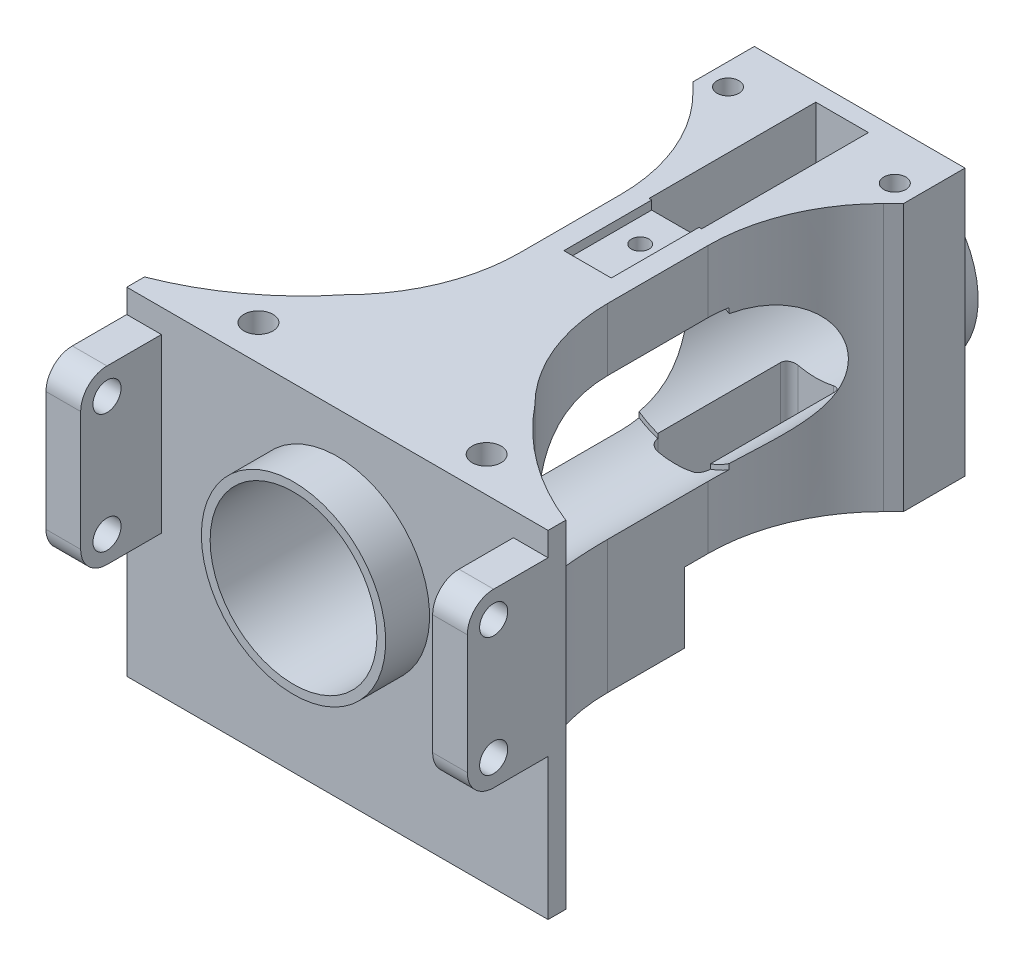
SolidWorks part; units mm, degrees
material "6061 合金"
ref_plane "前视基准面" through (0, 0, 0) normal (0, 0, 1) x (1, 0, 0)
ref_plane "上视基准面" through (0, 0, 0) normal (0, 1, 0) x (1, 0, 0)
ref_plane "右视基准面" through (0, 0, 0) normal (1, 0, 0) x (0, 0, -1)
sketch "草图1" plane through (0, 0, 0) normal (0, 0, 1) x (1, 0, 0)
  line L1 (-24, -15.2) -> (24, -15.2)
  line L2 (-24, -15.2) -> (-24, 15.2)
  line L3 (-24, 15.2) -> (24, 15.2)
  line L4 (24, -15.2) -> (24, 15.2)
  line L5 (-24, -15.2) -> (24, 15.2) construction
  line L6 (-24, 15.2) -> (24, -15.2) construction
  circle A0 centre (0, 0) radius 9
  point P0 (0, 0)
  dimension "D3" = 18
  dimension "D1" = 48
  dimension "D2" = 30.4
extrude "凸台-拉伸1" add sketch "草图1" along normal blind 65
sketch "草图2" plane through (0, 0, 65) normal (0, 0, 1) x (1, 0, 0)
  circle A0 centre (0, 0) radius 9.5
  dimension "D1" = 19
extrude "切除-拉伸1" cut sketch "草图2" against normal offset from surface (49 mm away) 16 up to face at (0, 0, 0)
sketch "草图4" plane through (0, 15.2, 0) normal (0, 1, 0) x (1, 0, 0)
  line L0 (-24, 9) -> (-10.8579, -4.1421)
  line L1 (-24, -65) -> (-24, 0) construction
  line L2 (-5, -18.2843) -> (-5, -29.7157)
  line L3 (-10.8579, -43.8579) -> (-24, -57) construction
  line L4 (-24, -57) -> (-24, 9) construction
  line L5 (0, 0) -> (0, -65) construction
  line L6 (24, -65) -> (-24, -65) construction
  line L7 (-24, -65) -> (-24, -62) construction
  line L8 (-24, -62) -> (-21, -62) construction
  line L9 (24, 0) -> (-24, 0) construction
  line L10 (10.8579, -43.8579) -> (24, -57) construction
  line L11 (5, -18.2843) -> (5, -29.7157)
  line L12 (24, 9) -> (10.8579, -4.1421)
  line L13 (24, -57) -> (24, 9) construction
  line L14 (35.5, -24) -> (-35.5, -24) construction
  line L15 (9.5, -2.5) -> (-9.5, -2.5) construction
  line L16 (24, -53.4842) -> (24, 9)
  line L17 (-24, -53.4842) -> (-24, 9)
  arc A2 (5, -18.2843) -> (10.8579, -4.1421) centre (25, -18.2843) cw
  arc A3 (10.8579, -43.8579) -> (5, -29.7157) centre (25, -29.7157) cw
  arc A4 (-5, -29.7157) -> (-10.8579, -43.8579) centre (-25, -29.7157) cw
  arc A5 (-10.8579, -4.1421) -> (-5, -18.2843) centre (-25, -18.2843) cw
  circle A6 centre (-35.5, -24) radius 30 construction
  circle A7 centre (35.5, -24) radius 30 construction
  circle A8 centre (9.5, -2.5) radius 1.2 construction
  circle A9 centre (-9.5, -2.5) radius 1.2 construction
  arc A10 (-10.8579, -43.8579) -> (-24, -53.4842) centre (-35.5, -24) cw
  arc A11 (10.8579, -43.8579) -> (24, -53.4842) centre (35.5, -24) ccw
  point P12 (-5, -24)
  point P26 (5, -10)
  point P29 (5, -38)
  point P32 (-5, -38)
  point P35 (-5, -10)
  point P36 (0, -24)
  point P41 (0, -2.5)
  dimension "D3" = 24
  dimension "D7" = 20
  dimension "D4" = 60
  dimension "D11" = 2.4
  dimension "D1" = 3
  dimension "D2" = 3
  dimension "D5" = 10
  dimension "D6" = 10
  dimension "D8" = 71
  dimension "D9" = 2.5
  dimension "D10" = 19
  dimension "D12" = 135
extrude "切除-拉伸3" cut sketch "草图4" against normal through all
sketch "草图6" plane through (0, 15.2, 0) normal (0, 1, 0) x (1, 0, 0)
  line L0 (0, 0) -> (0, -1) construction
  line L1 (-2, -1) -> (2, -1)
  line L2 (-3, -2) -> (-3, -16)
  line L3 (-2, -17) -> (2, -17)
  line L4 (3, -2) -> (3, -16)
  line L8 (-5, -18.2843) -> (5, -18.2843) construction
  arc A0 (-3, -16) -> (-2, -17) centre (-2, -16) ccw
  arc A1 (2, -17) -> (3, -16) centre (2, -16) ccw
  arc A2 (2, -1) -> (3, -2) centre (2, -2) cw
  arc A3 (-2, -1) -> (-3, -2) centre (-2, -2) ccw
  point P9 (-3, -17)
  point P14 (3, -1)
  point P17 (-3, -1)
  dimension "D4" = 1
  dimension "D1" = 1
  dimension "D2" = 16
  dimension "D3" = 6
extrude "切除-拉伸5" cut sketch "草图6" along normal through all from surface at -30.4 starting at face at (0, -15.2, 30.7635)
sketch "草图12" plane through (0, -15.2, 0) normal (0, -1, 0) x (1, 0, 0)
  line L0 (-5, 18.2843) -> (5, 18.2843)
  line L12 (-15, 0) -> (15, 0)
  line L14 (15, 0) -> (10.8579, 4.1421)
  line L15 (5, 18.2843) -> (5, 29.7157)
  line L17 (24, 53.4842) -> (24, 65)
  line L18 (24, 65) -> (-24, 65)
  line L19 (-24, 65) -> (-24, 53.4842)
  line L21 (-5, 29.7157) -> (-5, 18.2843)
  line L22 (-10.8579, 4.1421) -> (-15, 0)
  line L24 (-15, 0) -> (15, 0) construction
  line L26 (15, 0) -> (10.8579, 4.1421) construction
  line L27 (5, 18.2843) -> (5, 29.7157)
  line L29 (24, 53.4842) -> (24, 65)
  line L30 (24, 65) -> (-24, 65)
  line L31 (-24, 65) -> (-24, 53.4842)
  line L33 (-5, 29.7157) -> (-5, 18.2843)
  line L34 (-10.8579, 4.1421) -> (-15, 0) construction
  arc A4 (5, 18.2843) -> (10.8579, 4.1421) centre (25, 18.2843) ccw
  arc A5 (10.8579, 43.8579) -> (5, 29.7157) centre (25, 29.7157) ccw
  arc A6 (-5, 29.7157) -> (-10.8579, 43.8579) centre (-25, 29.7157) ccw
  arc A7 (-10.8579, 4.1421) -> (-5, 18.2843) centre (-25, 18.2843) ccw
  arc A8 (5, 18.2843) -> (10.8579, 4.1421) centre (25, 18.2843) ccw construction
  arc A9 (10.8579, 43.8579) -> (5, 29.7157) centre (25, 29.7157) ccw
  arc A10 (-5, 29.7157) -> (-10.8579, 43.8579) centre (-25, 29.7157) ccw
  arc A11 (-10.8579, 4.1421) -> (-5, 18.2843) centre (-25, 18.2843) ccw construction
  arc A14 (24, 53.4842) -> (10.8579, 43.8579) centre (35.5, 24) ccw
  arc A15 (24, 53.4842) -> (10.8579, 43.8579) centre (35.5, 24) ccw
  arc A16 (-10.8579, 43.8579) -> (-24, 53.4842) centre (-35.5, 24) ccw
  arc A17 (-10.8579, 43.8579) -> (-24, 53.4842) centre (-35.5, 24) ccw
  dimension "D1" = 0
extrude "凸台-拉伸4" add sketch "草图12" along normal blind 8
sketch "草图11" plane through (0, 15.2, 0) normal (0, 1, 0) x (1, 0, 0)
  line L0 (13, -51.5) -> (-13, -51.5) construction
  line L1 (0, -51.5) -> (0, 0) construction
  circle A0 centre (13, -51.5) radius 1.65
  circle A1 centre (-13, -51.5) radius 1.65
  dimension "D3" = 3.3
  dimension "D1" = 51.5
  dimension "D2" = 26
extrude "切除-拉伸9" cut sketch "草图11" against normal through all
cosmetic thread "装饰螺纹线5" parameters "D2"=4
cosmetic thread "装饰螺纹线6" parameters "D2"=4
cosmetic thread "装饰螺纹线7" parameters "D2"=4
cosmetic thread "装饰螺纹线8" parameters "D2"=4
sketch "草图14" plane through (0, -23.2, 0) normal (0, -1, 0) x (1, 0, 0)
  line L0 (-5, 24) -> (5, 24) construction
  line L1 (-5, 29.7157) -> (-5, 18.2843) construction
  line L2 (5, 18.2843) -> (5, 29.7157) construction
  circle A0 centre (0, 24) radius 1.65
  dimension "D1" = 3.3
extrude "切除-拉伸10" cut sketch "草图14" against normal blind 11
cosmetic thread "装饰螺纹线9" parameters "D2"=4
sketch "草图15" plane through (0, 15.2, 0) normal (0, 1, 0) x (1, 0, 0)
  line L0 (24, -65) -> (-24, -65) construction
  line L1 (20.05, -65) -> (-20.05, -65)
  line L2 (20.05, -65) -> (20.05, -55.5)
  line L3 (20.05, -55.5) -> (-20.05, -55.5)
  line L4 (-20.05, -65) -> (-20.05, -55.5)
  line L5 (0, 0) -> (0, -55.5) construction
  circle A0 centre (-13, -51.5) radius 1.65 construction
  dimension "D1" = 40.1
  dimension "D2" = 4
extrude "切除-拉伸11" cut sketch "草图15" against normal through all
sketch "草图17" plane through (24, 0, 0) normal (1, 0, 0) x (0, 0, -1)
  line L0 (-53.4842, -23.2) -> (-65, -23.2) construction
  line L1 (-65, 15.2) -> (-53.4842, 15.2) construction
  line L2 (-61.7, 9.5) -> (-61.7, -4.1) construction
  line L3 (-61.7, 2.7) -> (-55.5, 2.7) construction
  line L4 (-55.5, -23.2) -> (-55.5, -7.1)
  line L5 (-55.5, -7.1) -> (-61.7, -7.1)
  line L6 (-64.7, -4.1) -> (-64.7, 9.5)
  line L9 (-64.7, 15.2) -> (-93.9, 15.2)
  line L10 (-93.9, 15.2) -> (-93.9, -23.2)
  line L11 (-93.9, -23.2) -> (-55.5, -23.2)
  line L12 (-55.5, -23.2) -> (-55.5, 15.2) construction
  line L13 (-61.7, 12.5) -> (-55.5, 12.5)
  line L14 (-55.5, 12.5) -> (-55.5, 15.2)
  line L15 (-55.5, 15.2) -> (-64.7, 15.2)
  circle A0 centre (-61.7, 9.5) radius 1.6
  circle A1 centre (-61.7, -4.1) radius 1.6
  arc A3 (-61.7, -7.1) -> (-64.7, -4.1) centre (-61.7, -4.1) cw
  arc A4 (-61.7, 12.5) -> (-64.7, 9.5) centre (-61.7, 9.5) ccw
  dimension "D3" = 3.2
  dimension "D4" = 3
  dimension "D1" = 13.6
  dimension "D2" = 6.2
  dimension "D6" = 12.5
extrude "切除-拉伸13" cut sketch "草图17" against normal through all
sketch "草图19" plane through (0, -15.2, 0) normal (0, -1, 0) x (1, 0, 0)
  line L0 (-10.8579, 4.1421) -> (-15, 0) construction
  line L1 (-15, 0) -> (-12, 0)
  line L2 (-15, 0) -> (-15, 3)
  line L3 (-15, 3) -> (-12, 3)
  line L4 (-12, 0) -> (-12, 3)
  line L5 (15, 0) -> (10.8579, 4.1421) construction
  line L6 (15, 0) -> (12, 0)
  line L7 (15, 0) -> (15, 3)
  line L8 (15, 3) -> (12, 3)
  line L9 (12, 0) -> (12, 3)
  dimension "D1" = 3
extrude "切除-拉伸14" cut sketch "草图19" against normal through all
sketch "草图21" plane through (0, 0, 18.2843) normal (0, 0, -1) x (-1, 0, 0)
  line L1 (5, -23.2) -> (-5, -23.2)
  line L2 (5, -23.2) -> (5, -15.2)
  line L3 (5, -15.2) -> (-5, -15.2)
  line L4 (-5, -23.2) -> (-5, -15.2)
  line L5 (0, -15.2) -> (0, -23.2) construction
  line L6 (5, -19.2) -> (-5, -19.2) construction
  point P164 (0, -19.2)
extrude "切除-拉伸16" cut sketch "草图21" against normal blind 2.7
sketch "草图24" plane through (0, -15.2, 0) normal (0, -1, 0) x (1, 0, 0)
  line L0 (-12, 1.5) -> (12, 1.5) construction
  line L1 (-12, 0) -> (-12, 3) construction
  line L2 (12, 3) -> (12, 0) construction
  line L3 (-12, 0) -> (12, 0) construction
  circle A0 centre (-9.5, 1.5) radius 1.25
  circle A1 centre (9.5, 1.5) radius 1.25
  dimension "D2" = 2.5
  dimension "D3" = 2.5
  dimension "D4" = 2.5
  dimension "D1" = 1.5
extrude "切除-拉伸17" cut sketch "草图24" against normal through all
cosmetic thread "装饰螺纹线10" parameters "D2"=3
cosmetic thread "装饰螺纹线11" parameters "D2"=3
sketch "草图25" plane through (0, 0, 55.5) normal (0, 0, 1) x (1, 0, 0)
  circle A0 centre (0, 0) radius 9.5 construction
  circle A1 centre (0, 0) radius 9.5
  circle A2 centre (0, 0) radius 10.5
  dimension "D1" = 21
extrude "凸台-拉伸6" add sketch "草图25" along normal blind 86.25
sketch "草图27" plane through (-24, 0, 0) normal (-1, 0, 0) x (0, 0, 1)
  line L0 (141.75, -10.5) -> (141.75, 10.5) construction
  line L1 (141.75, 0) -> (0, 0) construction
  circle A0 centre (129.75, 0) radius 4
  circle A1 centre (78.75, 0) radius 4
  dimension "D1" = 8
  dimension "D2" = 12
  dimension "D3" = 63
extrude "切除-拉伸18" cut sketch "草图27" against normal through all
sketch "草图28" plane through (0, 15.2, 0) normal (0, -1, 0) x (1, 0, 0)
  line L0 (10.5, 141.75) -> (-10.5, 141.75) construction
  line L1 (-3.2, 141.75) -> (3.2, 141.75)
  line L2 (-3.2, 141.75) -> (-3.2, 139.55)
  line L3 (-3.2, 139.55) -> (3.2, 139.55)
  line L4 (3.2, 141.75) -> (3.2, 139.55)
  arc A0 (-3.2, 139.55) -> (3.2, 139.55) centre (0, 139.55) ccw
  point P6 (0, 141.75)
  dimension "D1" = 2.2
  dimension "D2" = 6.4
extrude "切除-拉伸19" cut sketch "草图28" along normal blind 15 contours L1 L4 L3 L2 | A0 L3
sketch "草图29" plane through (0, 0, 64.7) normal (0, 0, 1) x (1, 0, 0)
  line L1 (-15.5041, 18.7333) -> (-32.4201, 18.7333)
  line L2 (-15.5041, 18.7333) -> (-15.5041, -13.4812)
  line L3 (-15.5041, -13.4812) -> (-32.4201, -13.4812)
  line L4 (-32.4201, 18.7333) -> (-32.4201, -13.4812)
  line L5 (28.7759, 18.7333) -> (13.164, 18.7333)
  line L6 (28.7759, 18.7333) -> (28.7759, -15.1124)
  line L7 (28.7759, -15.1124) -> (13.164, -15.1124)
  line L8 (13.164, 18.7333) -> (13.164, -15.1124)
extrude "切除-拉伸20" [suppressed] cut sketch "草图29" against normal up to surface (9.2 mm away)
sketch "草图33" plane through (0, 15.2, 0) normal (0, 1, 0) x (1, 0, 0)
  line L0 (3, -16) -> (3, -17)
  line L1 (3, -17) -> (-3, -17)
  line L2 (-3, -17) -> (-3, -16)
  line L3 (-3, -16) -> (3, -16)
extrude "切除-拉伸21" cut sketch "草图33" against normal up to surface (6.1861 mm away)
sketch "草图34" plane through (0, 15.2, 0) normal (0, 1, 0) x (1, 0, 0)
  line L0 (2.7, -17) -> (2.7, -27)
  line L1 (2.7, -17) -> (-2.7, -17)
  line L2 (2.7, -27) -> (-2.7, -27)
  line L3 (-2.7, -17) -> (-2.7, -27)
  line L4 (0, -17) -> (0, -1) construction
  line L7 (2, -1) -> (-2, -1) construction
  dimension "D1" = 5.4
  dimension "D2" = 16
  dimension "D3" = 10
extrude "切除-拉伸22" cut sketch "草图34" against normal blind 1
sketch "草图35" plane through (0, 14.2, 0) normal (0, 1, 0) x (1, 0, 0)
  line L0 (0, -17) -> (0, -21) construction
  line L1 (2.7, -17) -> (-2.7, -17) construction
  circle A0 centre (0, -21) radius 1
  dimension "D1" = 2
  dimension "D2" = 4
extrude "切除-拉伸23" cut sketch "草图35" against normal blind 6
cosmetic thread "装饰螺纹线12" parameters "D2"=2.5
sketch "草图36" plane through (0, 0, 0) normal (0, 0, -1) x (-1, 0, 0)
  line L4 (12, -15.2) -> (12, 15.2)
  line L5 (12, 15.2) -> (-12, 15.2)
  line L6 (-12, 15.2) -> (-12, -15.2)
  line L7 (-12, -15.2) -> (12, -15.2)
  line L8 (12, -15.2) -> (12, 15.2)
  line L9 (12, 15.2) -> (-12, 15.2)
  line L10 (-12, 15.2) -> (-12, -15.2)
  line L11 (-12, -15.2) -> (12, -15.2)
  circle A0 centre (0, 0) radius 9 construction
  circle A1 centre (0, 0) radius 9
  dimension "D1" = 0
extrude "凸台-拉伸8" add sketch "草图36" along normal blind 4
sketch "草图37" plane through (0, 0, -4) normal (0, 0, -1) x (-1, 0, 0)
  circle A0 centre (0, 0) radius 9
  circle A1 centre (0, 0) radius 10.5
  dimension "D1" = 18
  dimension "D2" = 21
extrude "凸台-拉伸9" add sketch "草图37" along normal blind 3
sketch "草图38" plane through (0, 15.2, 0) normal (0, 1, 0) x (1, 0, 0)
  line L1 (3, -2) -> (-3, -2)
  line L2 (3, -2) -> (3, 2)
  line L3 (3, 2) -> (-3, 2)
  line L4 (-3, -2) -> (-3, 2)
  dimension "D1" = 6
  dimension "D2" = 4
extrude "切除-拉伸25" cut sketch "草图38" against normal blind 8
sketch "草图39" plane through (0, 0, 141.75) normal (0, 0, 1) x (1, 0, 0)
  circle A0 centre (0, 0) radius 12.3126
extrude "切除-拉伸26" cut sketch "草图39" against normal offset from surface (81.25 mm away) 5
